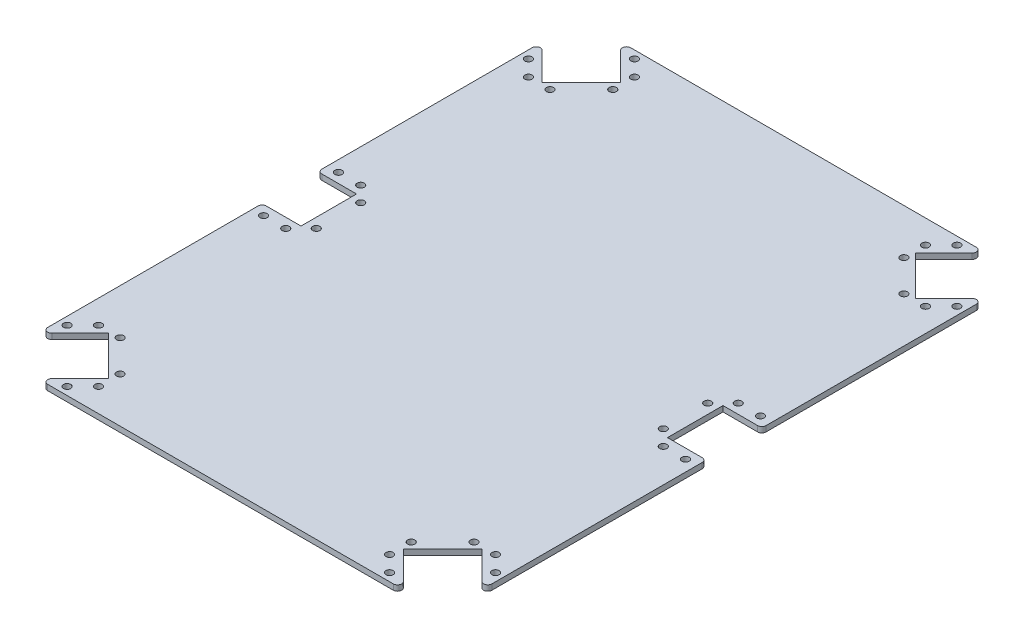
SolidWorks part; units mm, degrees
ref_plane "Front Plane" through (0, 0, 0) normal (0, 0, 1) x (1, 0, 0)
ref_plane "Top Plane" through (0, 0, 0) normal (0, 1, 0) x (1, 0, 0)
ref_plane "Right Plane" through (0, 0, 0) normal (1, 0, 0) x (0, 0, -1)
sketch "Sketch2" plane through (0, 0, 0) normal (0, 1, 0) x (1, 0, 0)
  line L0 (-80, 0) -> (80, 0) construction
  line L1 (-80, 105) -> (80, 105)
  line L2 (-80, 105) -> (-80, -105)
  line L3 (-80, -105) -> (80, -105)
  line L4 (80, 105) -> (80, -105)
  line L5 (80, 105) -> (0, 25) construction
  line L7 (0, 105) -> (0, -105) construction
  line L8 (52.4228, 88.7365) -> (48.5337, 92.6256) construction
  line L9 (48.5337, 92.6256) -> (52.4228, 96.5147) construction
  line L10 (52.4228, 96.5147) -> (58.0797, 102.1716) construction
  line L11 (58.0797, 102.1716) -> (60.9081, 105) construction
  circle A5 centre (52.4228, 88.7365) radius 1.3
  circle A6 centre (52.4228, 96.5147) radius 1.3
  circle A7 centre (58.0797, 102.1716) radius 1.3
  circle A8 centre (76, 13.5) radius 1.3
  circle A9 centre (68, 13.5) radius 1.3
  circle A10 centre (62.5, 8) radius 1.3
  circle A11 centre (62.5, -8) radius 1.3
  circle A12 centre (68, -13.5) radius 1.3
  circle A13 centre (76, -13.5) radius 1.3
  circle A14 centre (77.1716, 83.0797) radius 1.3
  circle A15 centre (71.5147, 77.4228) radius 1.3
  circle A16 centre (63.7365, 77.4228) radius 1.3
  circle A17 centre (77.1716, -83.0797) radius 1.3
  circle A18 centre (71.5147, -77.4228) radius 1.3
  circle A19 centre (63.7365, -77.4228) radius 1.3
  circle A20 centre (58.0797, -102.1716) radius 1.3
  circle A21 centre (52.4228, -96.5147) radius 1.3
  circle A22 centre (52.4228, -88.7365) radius 1.3
  circle A23 centre (-58.0797, 102.1716) radius 1.3
  circle A24 centre (-52.4228, 96.5147) radius 1.3
  circle A25 centre (-52.4228, 88.7365) radius 1.3
  circle A26 centre (-77.1716, 83.0797) radius 1.3
  circle A27 centre (-71.5147, 77.4228) radius 1.3
  circle A28 centre (-63.7365, 77.4228) radius 1.3
  circle A29 centre (-77.1716, -83.0797) radius 1.3
  circle A30 centre (-71.5147, -77.4228) radius 1.3
  circle A31 centre (-63.7365, -77.4228) radius 1.3
  circle A32 centre (-52.4228, -88.7365) radius 1.3
  circle A33 centre (-52.4228, -96.5147) radius 1.3
  circle A34 centre (-58.0797, -102.1716) radius 1.3
  circle A35 centre (-62.5, -8) radius 1.3
  circle A36 centre (-68, -13.5) radius 1.3
  circle A37 centre (-76, -13.5) radius 1.3
  circle A38 centre (-76, 13.5) radius 1.3
  circle A39 centre (-68, 13.5) radius 1.3
  circle A40 centre (-62.5, 8) radius 1.3
  point P0 (0, 0)
  point P27 (0, 0)
  dimension "D6" = 5.5
  dimension "D10" = 8
  dimension "D11" = 5.5
  dimension "D2" = 2.6
  dimension "D3" = 8
  dimension "D4" = 4
  dimension "D5" = 5.5
  dimension "D7" = 45
  dimension "D8" = 160
  dimension "D9" = 210
  dimension "D12" = 5.5
  dimension "D13" = 8
  dimension "D14" = 4
  dimension "D15" = 8
extrude "Boss-Extrude1" add sketch "Sketch2" along normal blind 2
sketch "Sketch3" plane through (0, 2, 0) normal (0, 1, 0) x (1, 0, 0)
  line L0 (0, -105) -> (0, 105) construction
  line L1 (-80, -105) -> (80, -105) construction
  line L2 (80, 105) -> (-80, 105) construction
  line L3 (-80, 0) -> (80, 0) construction
  line L4 (-80, 105) -> (-80, -105) construction
  line L5 (80, -105) -> (80, 105) construction
  line L6 (80, 105) -> (0, 25) construction
  line L7 (80, -10) -> (66, -10)
  line L8 (80, -10) -> (80, 10)
  line L9 (80, 10) -> (66, 10)
  line L10 (66, -10) -> (66, 10)
  line L11 (65.8579, 105) -> (53.1299, 92.2721)
  line L12 (53.1299, 92.2721) -> (67.2721, 78.1299)
  line L13 (67.2721, 78.1299) -> (80, 90.8579)
  line L14 (80, 90.8579) -> (80, 105)
  line L15 (80, 105) -> (65.8579, 105)
  line L16 (80, -90.8579) -> (80, -105)
  line L17 (67.2721, -78.1299) -> (80, -90.8579)
  line L18 (53.1299, -92.2721) -> (67.2721, -78.1299)
  line L19 (65.8579, -105) -> (53.1299, -92.2721)
  line L20 (80, -105) -> (65.8579, -105)
  line L21 (-80, 90.8579) -> (-80, 105)
  line L22 (-67.2721, 78.1299) -> (-80, 90.8579)
  line L23 (-53.1299, 92.2721) -> (-67.2721, 78.1299)
  line L24 (-65.8579, 105) -> (-53.1299, 92.2721)
  line L25 (-80, 105) -> (-65.8579, 105)
  line L26 (-80, 10) -> (-66, 10)
  line L27 (-66, -10) -> (-66, 10)
  line L28 (-80, -10) -> (-66, -10)
  line L29 (-80, -10) -> (-80, 10)
  line L30 (-67.2721, -78.1299) -> (-80, -90.8579)
  line L31 (-53.1299, -92.2721) -> (-67.2721, -78.1299)
  line L32 (-65.8579, -105) -> (-53.1299, -92.2721)
  line L33 (-80, -105) -> (-65.8579, -105)
  line L34 (-80, -90.8579) -> (-80, -105)
  dimension "D1" = 10
  dimension "D2" = 20
  dimension "D3" = 14
  dimension "D4" = 45
  dimension "D5" = 18
  dimension "D6" = 20
  dimension "D7" = 10
extrude "Cut-Extrude1" cut sketch "Sketch3" against normal up to surface (2 mm away) up to face at (0, 0, 0)
fillet "Fillet1" radius 1.5 12 edges at (-80, 1, 10) (-80, 1, -10) (-80, 1, 90.8579) (-65.8579, 1, 105) (65.8579, 1, 105) (80, 1, 90.8579) (80, 1, 10) (80, 1, -10) (80, 1, -90.8579) (65.8579, 1, -105) (-80, 1, -90.8579) (-65.8579, 1, -105)
